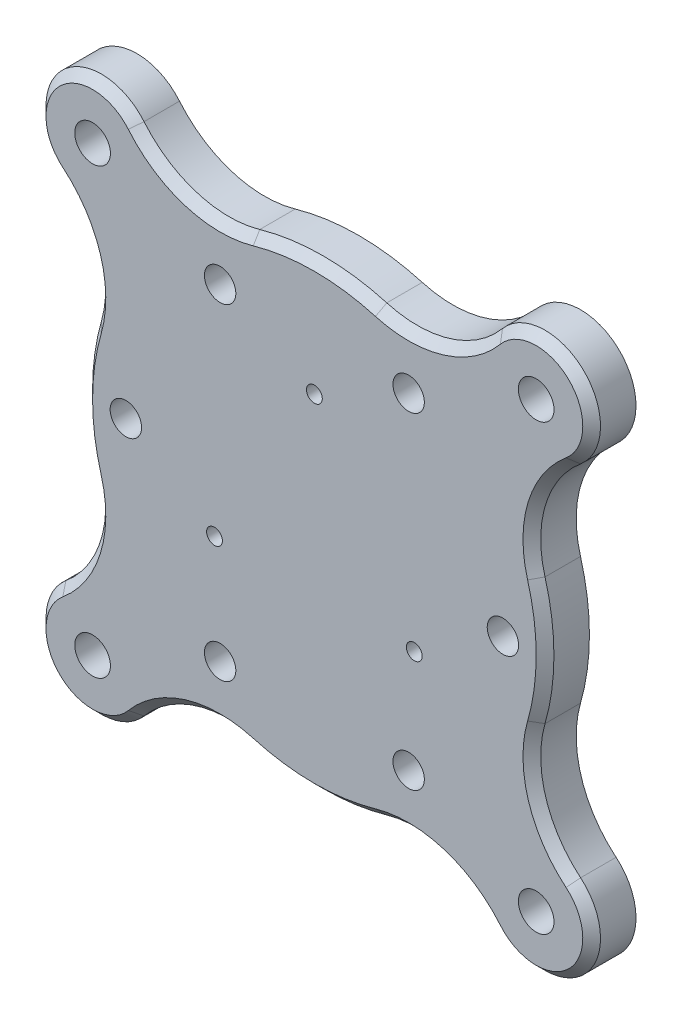
SolidWorks part; units mm, degrees
material "6061-T6 (SS)"
ref_plane "Front Plane" through (0, 0, 0) normal (0, 0, 1) x (1, 0, 0)
ref_plane "Top Plane" through (0, 0, 0) normal (0, 1, 0) x (1, 0, 0)
ref_plane "Right Plane" through (0, 0, 0) normal (1, 0, 0) x (0, 0, -1)
sketch "Sketch1" plane through (0, 0, 0) normal (0, 0, 1) x (1, 0, 0)
  circle A0 centre (0, 0) radius 53.975
  dimension "D1" = 107.95
extrude "Boss-Extrude1" add sketch "Sketch1" along normal blind 6.35
hole_wizard "CSK for #8 Flat Head Machine Screw1" positions "Sketch2" profile "Sketch3" countersink size "#8" standard "ANSI Inch" end condition through all
sketch "Sketch2" plane through (0, 0, 0) normal (0, 0, -1) x (-1, 0, 0)
  line L0 (-13.4937, 23.3719) -> (0, 0) construction
  line L1 (0, 0) -> (0, 26.9875) construction
  circle A0 centre (0, 0) radius 26.9875
  point P5 (-13.4937, 23.3719)
  dimension "D1" = 53.975
  dimension "D2" = 30
sketch "Sketch3" plane through (13.4937, 23.3719, 0) normal (1, 0, 0) x (0, 1, 0)
  line L0 (0, 0) -> (0, 6.35)
  line L1 (0, 6.35) -> (2.2479, 6.35)
  line L2 (2.2479, 6.35) -> (2.2479, 3.0265)
  line L3 (2.2479, 3.0265) -> (4.8788, 0)
  line L5 (4.8788, 0) -> (0, 0)
  line L6 (-2.2479, 3.0265) -> (-4.8788, 0) construction
  line L11 (0, -6.35) -> (0, 107.95) construction
  dimension "Thru Hole Dia." = 4.4958
  dimension "Thru Hole Depth" = 6.35
  dimension "Near C'Sink Dia." = 9.7576
  dimension "Near C'Sink Angle" = 82
pattern_circular "CirPattern1" count 6 over 360 about axis through (0, 0, 0) along (0, 0, 1) of "CSK for #8 Flat Head Machine Screw1"
hole_wizard "#10 Clearance Hole1" positions "Sketch4" profile "Sketch5" hole size "#10" standard "ANSI Inch" end condition through all
sketch "Sketch4" plane through (0, 0, 6.35) normal (0, 0, 1) x (1, 0, 0)
  line L0 (0, 44.9013) -> (0, 0) construction
  line L1 (0, 0) -> (31.75, 31.75) construction
  circle A0 centre (0, 0) radius 44.9013
  point P9 (31.75, 31.75)
  dimension "D1" = 31.75
  dimension "D2" = 45
sketch "Sketch5" plane through (31.75, 31.75, 6.35) normal (1, 0, 0) x (0, -1, 0)
  line L0 (0, 0) -> (0, 6.35)
  line L1 (0, 6.35) -> (2.5527, 6.35)
  line L2 (2.5527, 6.35) -> (2.5527, 0)
  line L5 (2.5527, 0) -> (0, 0)
  line L11 (0, -6.35) -> (0, 107.95) construction
  dimension "Thru Hole Dia." = 5.1054
  dimension "Thru Hole Depth" = 6.35
pattern_circular "CirPattern2" count 4 over 360 about axis through (0, 0, 0) along (0, 0, 1) of "#10 Clearance Hole1"
hole_wizard "#4-40 Tapped Hole1" positions "Sketch6" profile "Sketch7" tap size "#4-40" standard "ANSI Inch" end condition through all
sketch "Sketch6" plane through (0, 0, 6.35) normal (0, 0, 1) x (1, 0, 0)
  circle A0 centre (0, 0) radius 16.51
  point P5 (0, 16.51)
  dimension "D1" = 33.02
sketch "Sketch7" plane through (0, 16.51, 6.35) normal (1, 0, 0) x (0, -1, 0)
  line L0 (0, 0) -> (0, 6.35)
  line L1 (0, 6.35) -> (1.1303, 6.35)
  line L2 (1.1303, 6.35) -> (1.1303, 0)
  line L5 (1.1303, 0) -> (0, 0)
  line L11 (0, -6.35) -> (0, 107.95) construction
  dimension "Thru Tap Drill Dia." = 2.2606
  dimension "Thru Tap Drill Depth" = 6.35
cosmetic thread "Hole Thread1" parameters "D2"=2.8448
pattern_circular "CirPattern3" count 3 over 360 about axis through (0, 0, 0) along (0, 0, 1) of "#4-40 Tapped Hole1"
sketch "Sketch9" plane through (0, 0, 0) normal (0, 0, -1) x (-1, 0, 0)
  line L0 (-37.3627, 37.3627) -> (-38.1661, 38.1661)
  line L1 (38.1661, 38.1661) -> (37.3627, 37.3627)
  arc A0 (-25.655, 36.8348) -> (-37.3627, 37.3627) centre (-31.75, 31.75) ccw
  arc A1 (9.0933, 31.7432) -> (-9.0933, 31.7432) centre (0, 0) ccw
  arc A2 (37.3627, 37.3627) -> (25.655, 36.8348) centre (31.75, 31.75) ccw
  circle A5 centre (0, 0) radius 53.975 construction
  arc A6 (38.1661, 38.1661) -> (-38.1661, 38.1661) centre (0, 0) ccw
  arc A8 (9.0933, 31.7432) -> (25.655, 36.8348) centre (13.4651, 47.0044) ccw
  arc A9 (-25.655, 36.8348) -> (-9.0933, 31.7432) centre (-13.4651, 47.0044) ccw
  dimension "D1" = 15.875
  dimension "D2" = 33.02
  dimension "D3" = 15.875
extrude "Cut-Extrude2" cut sketch "Sketch9" against normal through all
pattern_circular "CirPattern4" count 4 over 360 about axis through (0, 0, 0) along (0, 0, 1) of "Cut-Extrude2"
chamfer "Chamfer1" distance 1.27 angle 45 16 edges at (-33.02, 0, 6.35) (-31.8303, -18.13, 6.35) (-31.8303, 18.13, 6.35) (-37.3627, -37.3627, 6.35) (-37.3627, 37.3627, 6.35) (-18.13, -31.8303, 6.35) (-18.13, 31.8303, 6.35) (0, -33.02, 6.35) (0, 33.02, 6.35) (18.13, -31.8303, 6.35) (18.13, 31.8303, 6.35) (37.3627, -37.3627, 6.35) (37.3627, 37.3627, 6.35) (31.8303, -18.13, 6.35) (31.8303, 18.13, 6.35) (33.02, 0, 6.35)
